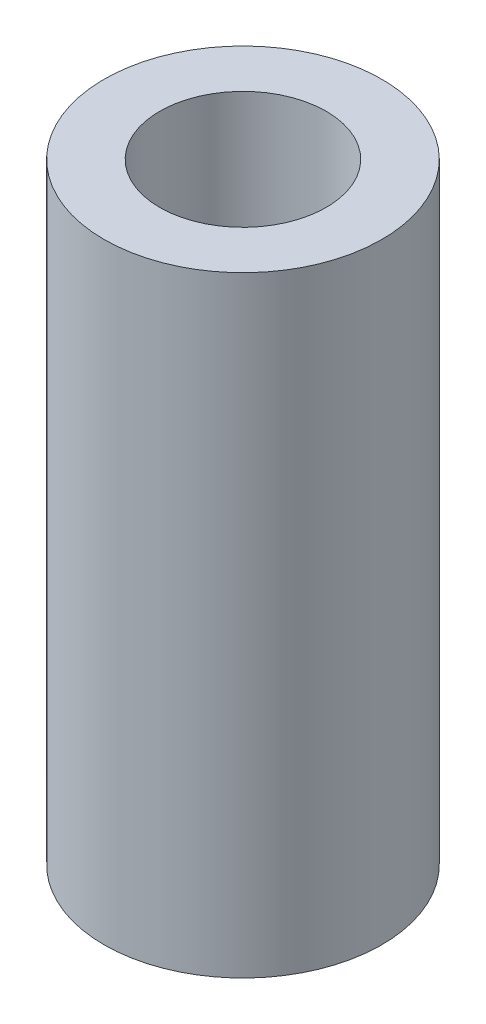
SolidWorks part; units mm, degrees
ref_plane "前视基准面" through (0, 0, 0) normal (0, 0, 1) x (1, 0, 0)
ref_plane "上视基准面" through (0, 0, 0) normal (0, 1, 0) x (1, 0, 0)
ref_plane "右视基准面" through (0, 0, 0) normal (1, 0, 0) x (0, 0, -1)
other "Configuration Table"
sketch "草图1" plane through (0, 0, 0) normal (0, 1, 0) x (1, 0, 0)
  circle A0 centre (0, 0) radius 2.5
  circle A1 centre (0, 0) radius 1.5
  point P5 (-0.0613, 0)
  dimension "D1" = 3
  dimension "D2" = 5
extrude "凸台-拉伸1" add sketch "草图1" along normal blind 11
